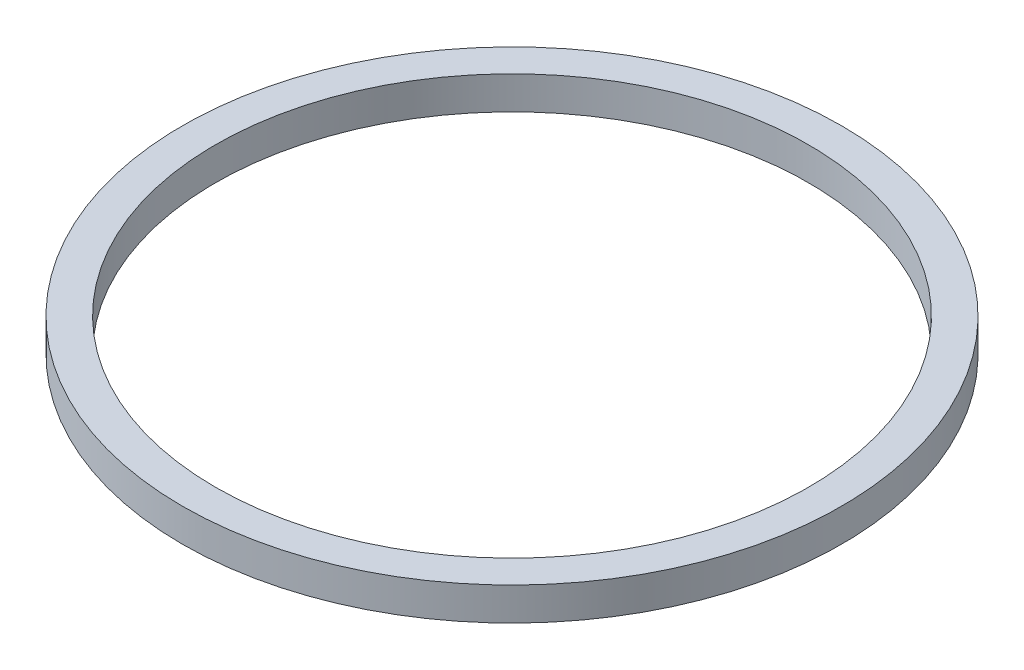
SolidWorks part; units mm, degrees
ref_plane "Ön Düzlem" through (0, 0, 0) normal (0, 0, 1) x (1, 0, 0)
ref_plane "Üst Düzlem" through (0, 0, 0) normal (0, 1, 0) x (1, 0, 0)
ref_plane "Sağ Düzlem" through (0, 0, 0) normal (1, 0, 0) x (0, 0, -1)
sketch "Çizim1" plane through (0, 0, 0) normal (0, 1, 0) x (1, 0, 0)
  circle A0 centre (0, 0) radius 10
  point P2 (0, 0)
  dimension "D1" = 20
extrude "Yükseklik-Ekstrüzyon1" add sketch "Çizim1" along normal blind 1
sketch "Çizim2" plane through (0, 1, 0) normal (0, 1, 0) x (1, 0, 0)
  circle A0 centre (0, 0) radius 9
  dimension "D1" = 18
extrude "Kes-Ekstrüzyon1" cut sketch "Çizim2" against normal blind 1
